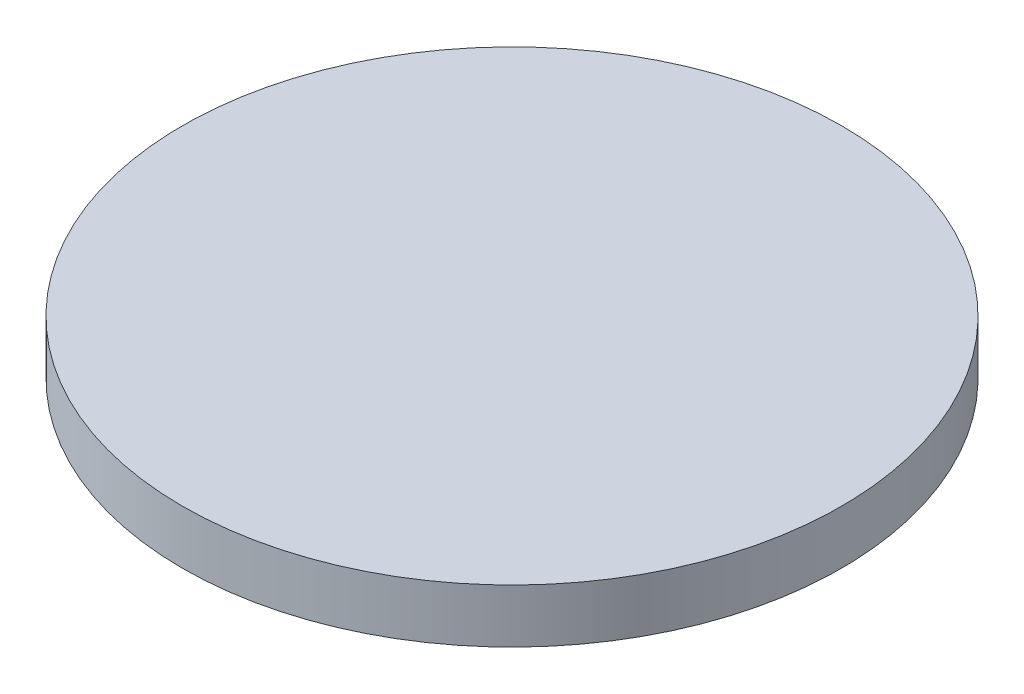
SolidWorks part; units mm, degrees
material "Pine"
ref_plane "Front" through (0, 0, 0) normal (0, 0, 1) x (1, 0, 0)
ref_plane "Top" through (0, 0, 0) normal (0, 1, 0) x (1, 0, 0)
ref_plane "Right" through (0, 0, 0) normal (1, 0, 0) x (0, 0, -1)
sketch "Sketch1" plane through (0, 0, 0) normal (0, 1, 0) x (1, 0, 0)
  circle A0 centre (0, 0) radius 101.2
extrude "Boss-Extrude1" add sketch "Sketch1" along normal blind 16.51 contours A0
